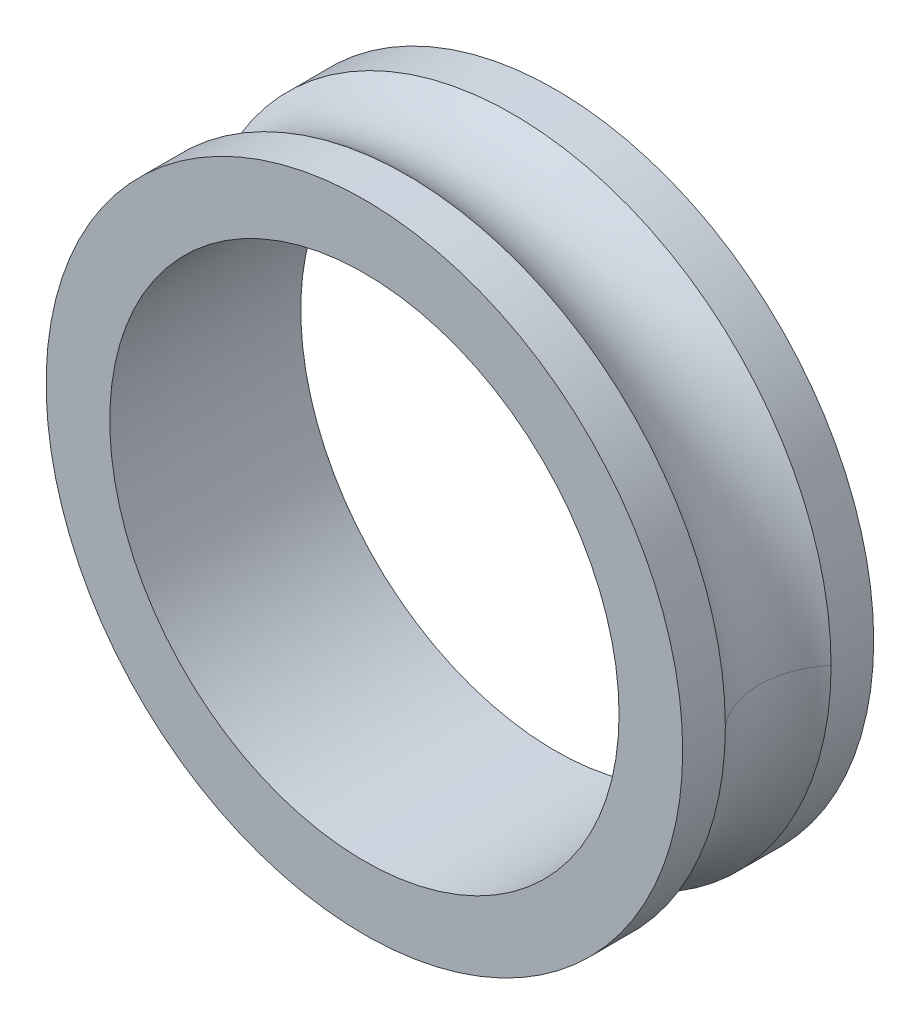
SolidWorks part; units mm, degrees
ref_plane "Front Plane" through (0, 0, 0) normal (0, 0, 1) x (1, 0, 0)
ref_plane "Top Plane" through (0, 0, 0) normal (0, 1, 0) x (1, 0, 0)
ref_plane "Right Plane" through (0, 0, 0) normal (1, 0, 0) x (0, 0, -1)
sketch "Sketch1" plane through (0, 0, 0) normal (0, 0, 1) x (1, 0, 0)
  circle A0 centre (0, 0) radius 20
  circle A1 centre (0, 0) radius 25
  dimension "D1" = 50
  dimension "D2" = 40
extrude "Boss-Extrude1" add sketch "Sketch1" along normal mid plane 15
sketch "Sketch4" plane through (0, 0, 0) normal (1, 0, 0) x (0, 0, -1)
  line L0 (-6.5, -30) -> (6.5, -30)
  circle A0 centre (0, -30) radius 6.5
  point P4 (0, 0)
  dimension "D1" = 13
  dimension "D2" = 30
sweep "Cut-Sweep2" cut profiles "Sketch4" path edge at (25, 0, 7.5)
